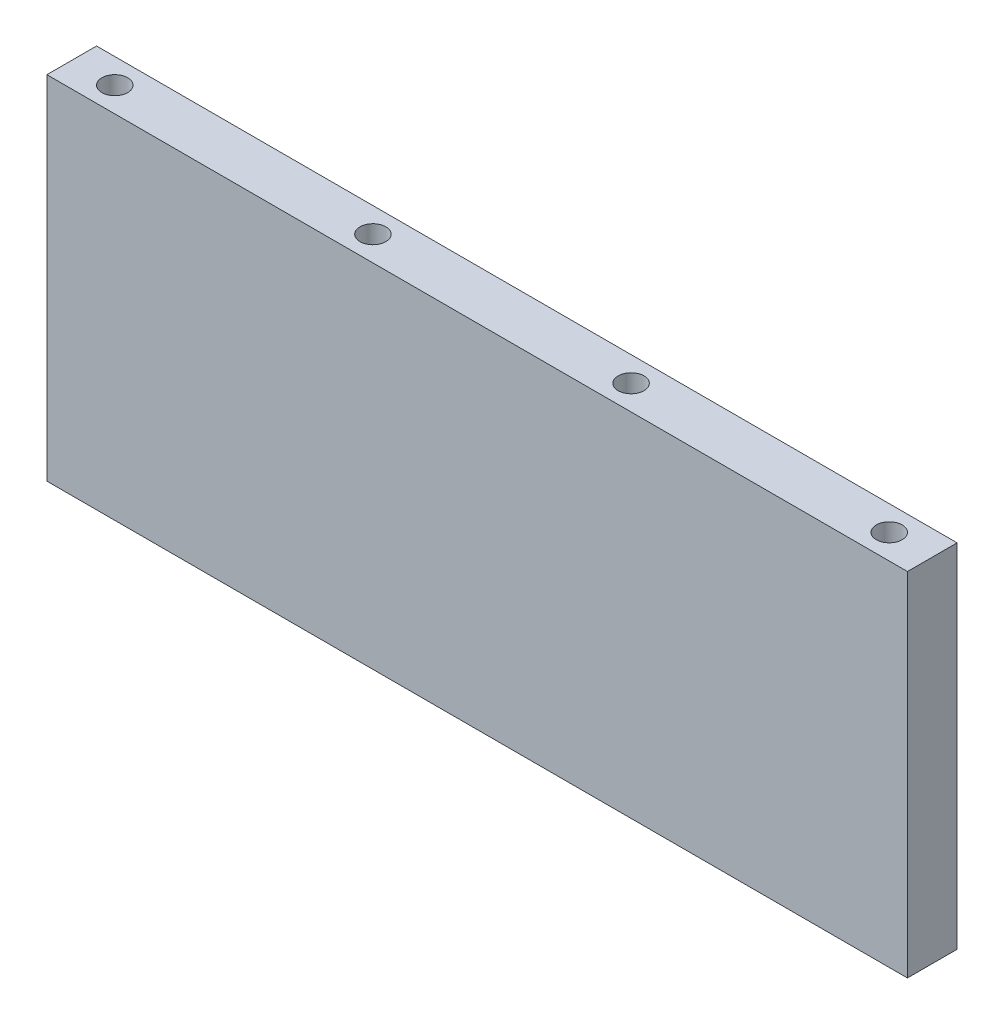
SolidWorks part; units mm, degrees
material "6061 Alloy"
ref_plane "Front Plane" through (0, 0, 0) normal (0, 0, 1) x (1, 0, 0)
ref_plane "Top Plane" through (0, 0, 0) normal (0, 1, 0) x (1, 0, 0)
ref_plane "Right Plane" through (0, 0, 0) normal (1, 0, 0) x (0, 0, -1)
sketch "Sketch1" plane through (0, 0, 0) normal (0, 0, 1) x (1, 0, 0)
  line L1 (0, 0) -> (110, 0)
  line L2 (0, 0) -> (0, 45)
  line L3 (0, 45) -> (110, 45)
  line L4 (110, 0) -> (110, 45)
  dimension "D1" = 110
  dimension "D2" = 45
extrude "Boss-Extrude1" add sketch "Sketch1" along normal blind 6.35
sketch "Sketch2" plane through (0, 45, 0) normal (0, 1, 0) x (1, 0, 0)
  line L0 (0, -6.35) -> (0, 0) construction
  line L1 (110, 0) -> (0, 0) construction
  point P0 (5.5, -3.175)
  point P1 (38.5, -3.175)
  point P2 (71.5, -3.175)
  point P3 (104.5, -3.175)
  dimension "D1" = 5.5
  dimension "D2" = 33
  dimension "D3" = 33
  dimension "D4" = 33
  dimension "D5" = 3.175
hole_wizard "M4x0.7 Tapped Hole1" positions "Sketch4" profile "Sketch3" tap size "M4x0.7" standard "ANSI Metric" end condition through all
sketch "Sketch4" plane through (0, 45, 0) normal (0, 1, 0) x (1, 0, 0)
  point P0 (5.5, -3.175)
  point P3 (38.5, -3.175)
  point P6 (71.5, -3.175)
  point P9 (104.5, -3.175)
cosmetic thread "Hole Thread1"
cosmetic thread "Hole Thread2"
cosmetic thread "Hole Thread3"
cosmetic thread "Hole Thread4"
sketch "Sketch3" plane through (5.5, 45, 3.175) normal (1, 0, 0) x (0, 0, 1)
  line L0 (0, 0) -> (0, 45)
  line L1 (0, 45) -> (1.65, 45)
  line L2 (1.65, 45) -> (1.65, 0)
  line L5 (1.65, 0) -> (0, 0)
  line L11 (0, -6.35) -> (0, 107.95) construction
  dimension "Thru Tap Drill Dia." = 3.3
  dimension "Thru Tap Drill Depth" = 45
